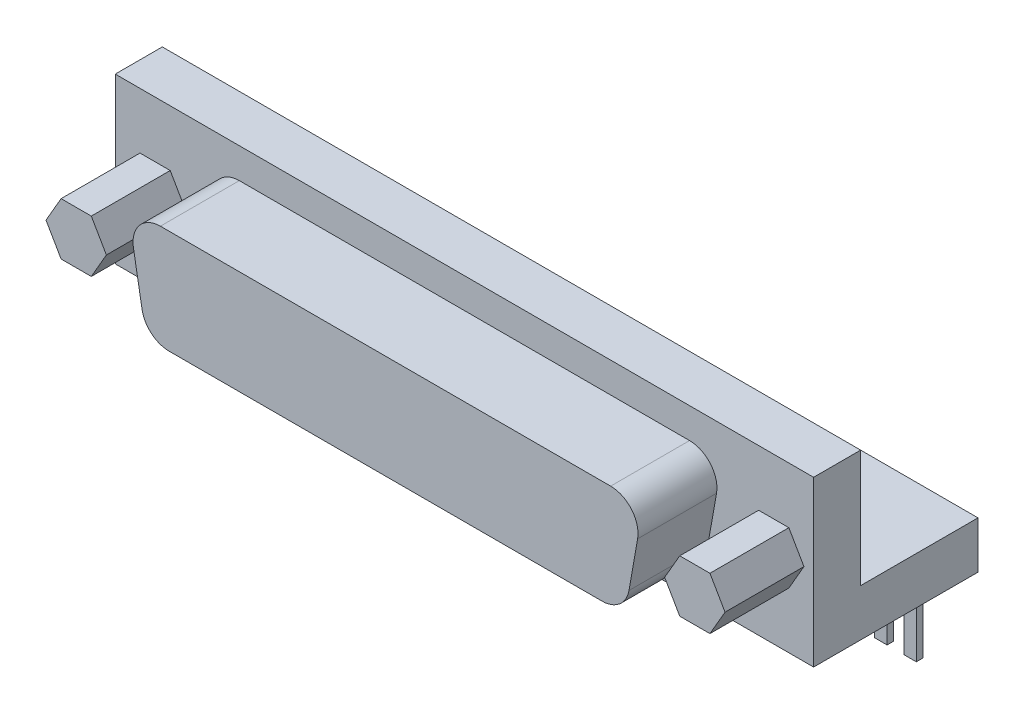
SolidWorks part; units mm, degrees
material "6061-T6 (SS)"
ref_plane "Front Plane" through (0, 0, 0) normal (0, 0, 1) x (1, 0, 0)
ref_plane "Top Plane" through (0, 0, 0) normal (0, 1, 0) x (1, 0, 0)
ref_plane "Right Plane" through (0, 0, 0) normal (1, 0, 0) x (0, 0, -1)
sketch "Sketch1" plane through (0, 0, 0) normal (1, 0, 0) x (0, 0, -1)
  line L1 (0, 0) -> (12.5, 0)
  line L2 (0, 0) -> (0, 12.5)
  line L3 (0, 12.5) -> (3.5774, 12.5)
  line L4 (12.5, 0) -> (12.5, 3.5774)
  line L7 (12.5, 3.5774) -> (3.5774, 3.5774)
  line L8 (3.5774, 12.5) -> (3.5774, 3.5774)
  point P1 (12.5, 3.5774)
  dimension "D1" = 12.5
  dimension "D2" = 12.5
extrude "Boss-Extrude1" add sketch "Sketch1" along normal blind 53.1
sketch "Sketch2" plane through (0, 0, 0) normal (0, 0, 1) x (1, 0, 0)
  line L0 (9.4328, 10.2) -> (43.6672, 10.2)
  line L1 (45.7184, 7.7555) -> (45.0599, 4.0211)
  line L2 (43.0087, 2.3) -> (10.0913, 2.3)
  line L3 (8.0401, 4.0211) -> (7.3816, 7.7555)
  line L4 (26.55, 10.2) -> (26.55, 12.5) construction
  line L5 (53.1, 12.5) -> (0, 12.5) construction
  line L6 (14.9307, 2.3) -> (14.9307, 0) construction
  line L7 (53.1, 0) -> (0, 0) construction
  line L8 (0, 12.5) -> (0, 0) construction
  arc A0 (43.6672, 10.2) -> (45.7184, 7.7555) centre (43.6672, 8.1172) cw
  arc A1 (45.0599, 4.0211) -> (43.0087, 2.3) centre (43.0087, 4.3828) cw
  arc A2 (10.0913, 2.3) -> (8.0401, 4.0211) centre (10.0913, 4.3828) cw
  arc A3 (9.4328, 10.2) -> (7.3816, 7.7555) centre (9.4328, 8.1172) ccw
  point P21 (0, 0)
  point P22 (29.8398, 2.3)
  point P23 (0, 0)
  point P24 (0, 0)
  point P25 (50.1543, 2.3)
  point P26 (39.7699, 2.655)
  point P27 (14.1984, 2.596)
  point P28 (9.7313, 2.3)
  dimension "D1" = 2.0828
  dimension "D3" = 38.4
  dimension "D2" = 7.9
  dimension "D4" = 10
extrude "Boss-Extrude2" add sketch "Sketch2" along normal blind 6
sketch "Sketch3" plane through (0, 0, 0) normal (0, -1, 0) x (1, 0, 0)
  line L0 (2.3955, -9.25) -> (3.6645, -9.75) construction
  line L1 (1.44, -9.25) -> (2.3955, -9.25)
  line L2 (1.44, -9.25) -> (1.44, -9.75)
  line L3 (1.44, -9.75) -> (2.3955, -9.75)
  line L4 (2.3955, -9.25) -> (2.3955, -9.75)
  line L5 (3.6645, -9.25) -> (4.62, -9.25)
  line L6 (3.6645, -9.25) -> (3.6645, -9.75)
  line L7 (3.6645, -9.75) -> (4.62, -9.75)
  line L8 (4.62, -9.25) -> (4.62, -9.75)
  line L9 (48.48, -9.25) -> (49.4355, -9.25)
  line L10 (48.48, -9.25) -> (48.48, -9.75)
  line L11 (48.48, -9.75) -> (49.4355, -9.75)
  line L12 (49.4355, -9.25) -> (49.4355, -9.75)
  line L13 (50.7045, -9.25) -> (51.66, -9.25)
  line L14 (50.7045, -9.25) -> (50.7045, -9.75)
  line L15 (50.7045, -9.75) -> (51.66, -9.75)
  line L16 (51.66, -9.25) -> (51.66, -9.75)
  line L17 (49.4355, -9.75) -> (50.7045, -9.25) construction
  line L18 (50.07, -9.5) -> (3.03, -9.5) construction
  line L19 (26.55, -9.5) -> (26.55, -12.5) construction
  line L20 (53.1, -12.5) -> (0, -12.5) construction
  line L21 (53.1, 0) -> (0, 0) construction
  point P24 (4.62, -9.0977)
  point P25 (3.6645, -9.75)
  dimension "D1" = 0.5
  dimension "D2" = 3.18
  dimension "D3" = 3.18
  dimension "D4" = 47.04
  dimension "D5" = 9.5
extrude "Boss-Extrude3" add sketch "Sketch3" along normal blind 5
sketch "Sketch4" plane through (0, 0, 0) normal (0, 0, 1) x (1, 0, 0)
  line L0 (3.03, 12.5) -> (3.03, 6.25) construction
  line L1 (4.178, 4.2616) -> (5.326, 6.25)
  line L2 (5.326, 6.25) -> (4.178, 8.2384)
  line L3 (4.178, 8.2384) -> (1.882, 8.2384)
  line L4 (1.882, 8.2384) -> (0.734, 6.25)
  line L5 (0.734, 6.25) -> (1.882, 4.2616)
  line L6 (1.882, 4.2616) -> (4.178, 4.2616)
  line L7 (51.218, 4.2616) -> (52.366, 6.25)
  line L8 (52.366, 6.25) -> (51.218, 8.2384)
  line L9 (51.218, 8.2384) -> (48.922, 8.2384)
  line L10 (48.922, 8.2384) -> (47.774, 6.25)
  line L11 (47.774, 6.25) -> (48.922, 4.2616)
  line L12 (48.922, 4.2616) -> (51.218, 4.2616)
  line L13 (53.1, 12.5) -> (0, 12.5) construction
  line L14 (3.03, 6.25) -> (3.03, 0) construction
  line L15 (53.1, 0) -> (0, 0) construction
  line L16 (3.03, 6.25) -> (26.55, 12.5) construction
  line L17 (26.55, 12.5) -> (50.07, 6.25) construction
  circle A0 centre (3.03, 6.25) radius 1.9884 construction
  circle A1 centre (50.07, 6.25) radius 1.9884 construction
  point P9 (1.5441, 6.25)
  point P24 (1.882, 4.2616)
  dimension "D1" = 47.04
extrude "Boss-Extrude4" add sketch "Sketch4" along normal blind 6
sketch "Sketch5" plane through (0, 0, 0) normal (0, -1, 0) x (1, 0, 0)
  line L1 (4.62, -9.25) -> (48.48, -9.25) construction
  line L2 (4.62, -9.25) -> (4.62, -9.75) construction
  line L3 (4.62, -9.75) -> (48.48, -9.75) construction
  line L4 (48.48, -9.25) -> (48.48, -9.75) construction
  line L5 (4.62, -9.25) -> (48.48, -9.75) construction
  line L6 (4.62, -9.75) -> (48.48, -9.25) construction
  point P0 (26.55, -9.5)
  point P5 (0, 0)
  point P7 (7.0027, -10.014)
  point P8 (8.6555, -11.1473)
  point P9 (0, 0)
ref_point "EAGLEREF"
